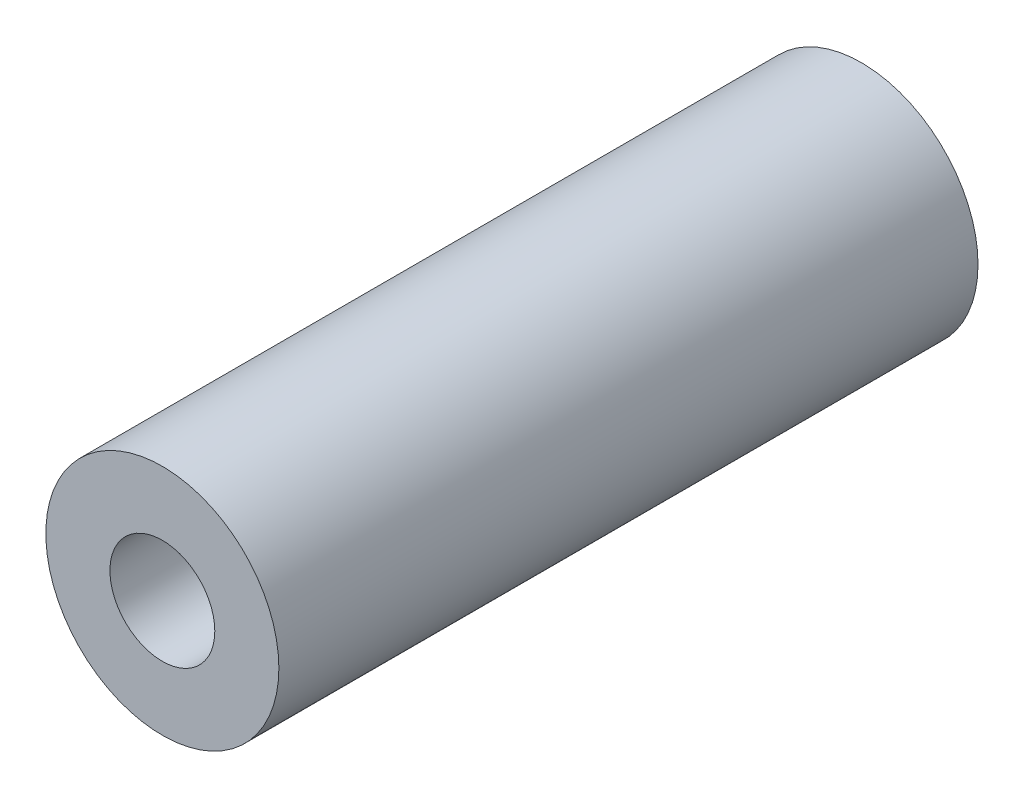
SolidWorks part; units mm, degrees
ref_plane "Спереди" through (0, 0, 0) normal (0, 0, 1) x (1, 0, 0)
ref_plane "Сверху" through (0, 0, 0) normal (0, 1, 0) x (1, 0, 0)
ref_plane "Справа" through (0, 0, 0) normal (1, 0, 0) x (0, 0, -1)
sketch "Эскиз1" plane through (0, 0, 0) normal (0, 0, 1) x (1, 0, 0)
  circle A0 centre (0, 0) radius 5
  circle A1 centre (0, 0) radius 2.25
  dimension "D1" = 4.5
  dimension "D2" = 10
extrude "Бобышка-Вытянуть1" add sketch "Эскиз1" along normal blind 30
